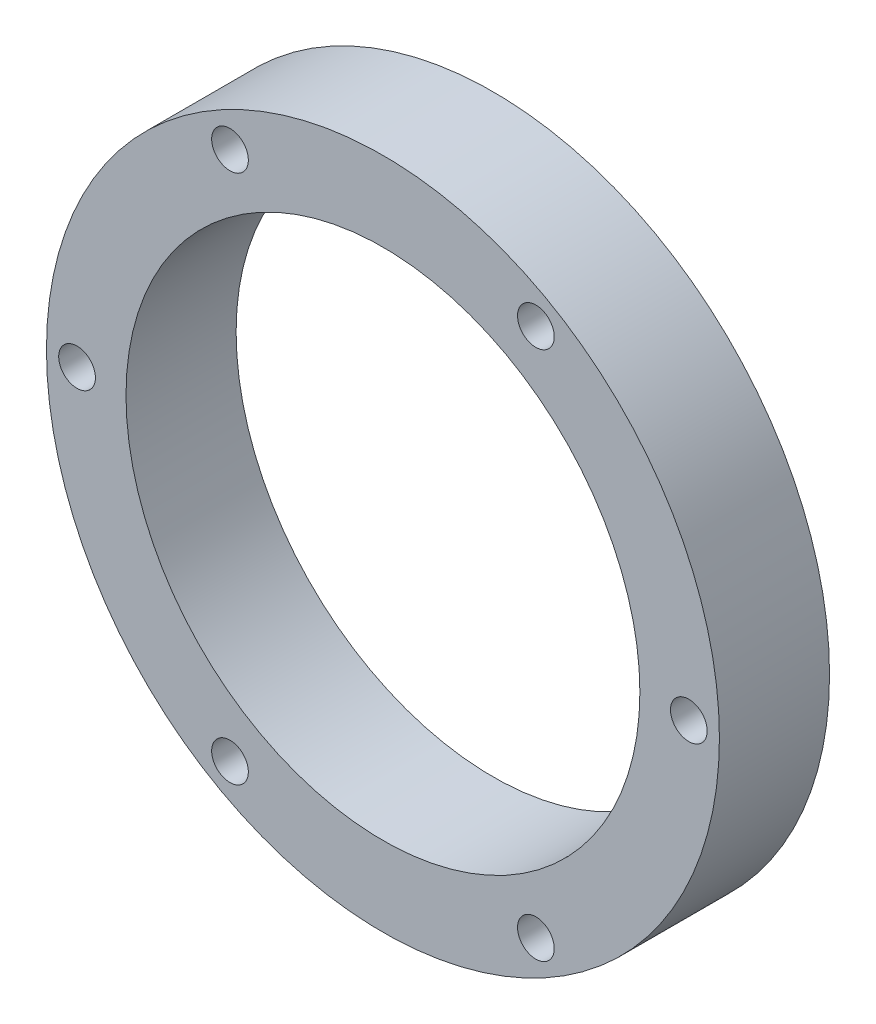
SolidWorks part; units mm, degrees
material "Acrylic (Medium-high impact)"
ref_plane "Front Plane" through (0, 0, 0) normal (0, 0, 1) x (1, 0, 0)
ref_plane "Top Plane" through (0, 0, 0) normal (0, 1, 0) x (1, 0, 0)
ref_plane "Right Plane" through (0, 0, 0) normal (1, 0, 0) x (0, 0, -1)
sketch "Sketch1" plane through (0, 0, 0) normal (0, 0, 1) x (1, 0, 0)
  line L0 (0, 34.8882) -> (0, -35.3531) construction
  line L1 (0, -35.3531) -> (0, 0) construction
  line L2 (0, 0) -> (-48.3544, 0) construction
  line L3 (-48.3544, 0) -> (47.9766, 0) construction
  line L4 (-26.5908, 46.0566) -> (27.6893, -47.9592) construction
  line L5 (27.6893, -47.9592) -> (0, 0) construction
  line L6 (0, 0) -> (21.8015, 37.7613) construction
  line L7 (0, 0) -> (-24.3439, -42.1648) construction
  circle A0 centre (0, 0) radius 27.5
  circle A2 centre (0, 0) radius 21
  circle A7 centre (0, 0) radius 25 construction
  circle A8 centre (-12.5, 21.6506) radius 1.5
  circle A9 centre (-25, 0) radius 1.5
  circle A10 centre (-12.5, -21.6506) radius 1.5
  circle A12 centre (12.5, -21.6506) radius 1.5
  circle A13 centre (25, 0) radius 1.5
  circle A14 centre (12.5, 21.6506) radius 1.5
  dimension "D2" = 60
  dimension "D4" = 3
  dimension "D5" = 3
  dimension "D3" = 60
extrude "Boss-Extrude1" add sketch "Sketch1" along normal blind 9
